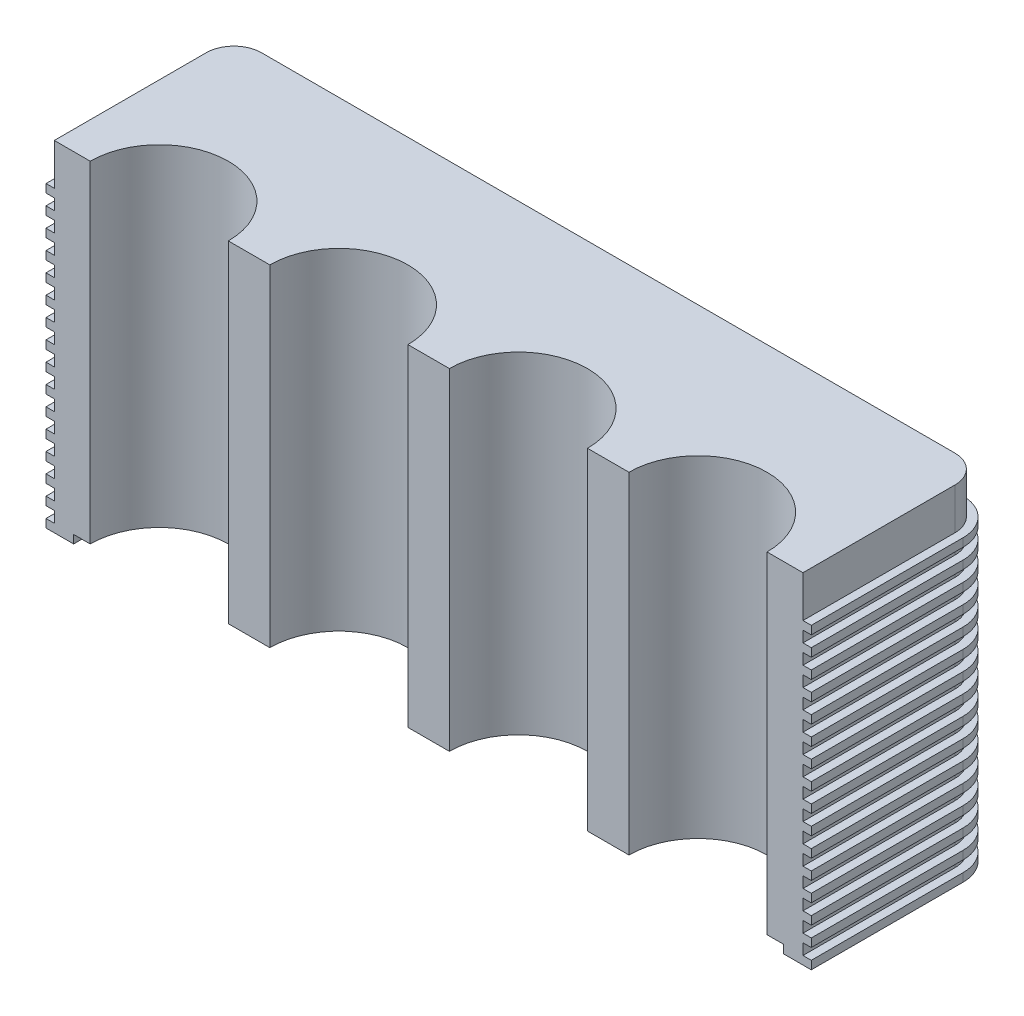
SolidWorks part; units mm, degrees
ref_plane "Front Plane" through (0, 0, 0) normal (0, 0, 1) x (1, 0, 0)
ref_plane "Top Plane" through (0, 0, 0) normal (0, 1, 0) x (1, 0, 0)
ref_plane "Right Plane" through (0, 0, 0) normal (1, 0, 0) x (0, 0, -1)
sketch "Sketch1" plane through (0, 0, 0) normal (0, 1, 0) x (1, 0, 0)
  line L0 (134.123, 69.5802) -> (135.5, 65) construction
  line L1 (0, 0) -> (13, 0)
  line L2 (0, 0) -> (0, 55)
  line L3 (10, 65) -> (261, 65)
  line L4 (271, 0) -> (271, 55)
  line L5 (135.5, 65) -> (135.5, 0) construction
  line L6 (258, 0) -> (271, 0)
  line L7 (193, 0) -> (208, 0)
  line L8 (63, 0) -> (78, 0)
  line L9 (128, 0) -> (143, 0)
  arc A0 (261, 65) -> (271, 55) centre (261, 55) cw
  arc A1 (10, 65) -> (0, 55) centre (10, 55) ccw
  arc A2 (258, 0) -> (208, 0) centre (233, 0) ccw
  arc A3 (193, 0) -> (143, 0) centre (168, 0) ccw
  arc A4 (78, 0) -> (128, 0) centre (103, 0) cw
  arc A5 (13, 0) -> (63, 0) centre (38, 0) cw
  point P7 (271, 65)
  point P10 (0, 65)
  dimension "D3" = 10
  dimension "D4" = 13
  dimension "D1" = 271
  dimension "D2" = 65
  dimension "D5" = 15
extrude "Boss-Extrude1" add sketch "Sketch1" along normal blind 120
sketch "Sketch3" plane through (0, 0, 0) normal (0, -1, 0) x (1, 0, 0)
  line L19 (274, 0) -> (274, -55)
  line L20 (261, -68) -> (10, -68)
  line L21 (-3, -55) -> (-3, 0)
  line L22 (274, 0) -> (274, -55)
  line L23 (261, -68) -> (10, -68)
  line L24 (-3, -55) -> (-3, 0)
  arc A8 (261, -68) -> (274, -55) centre (261, -55) ccw
  arc A9 (-3, -55) -> (10, -68) centre (10, -55) ccw
  arc A10 (261, -68) -> (274, -55) centre (261, -55) ccw
  arc A11 (-3, -55) -> (10, -68) centre (10, -55) ccw
  point P0 (0, 0)
  dimension "D1" = 3
sketch "Sketch5" plane through (0, 0, 0) normal (0, 1, 0) x (1, 0, 0)
  line L0 (-3, 0) -> (0, 0)
  line L1 (271, 0) -> (274, 0)
extrude "Extrude-Thin1" add sketch "Sketch3" along normal blind 3 thin
pattern_linear "LPattern2" count 16 spacing 7 along (0, 1, 0) of "Extrude-Thin1"
